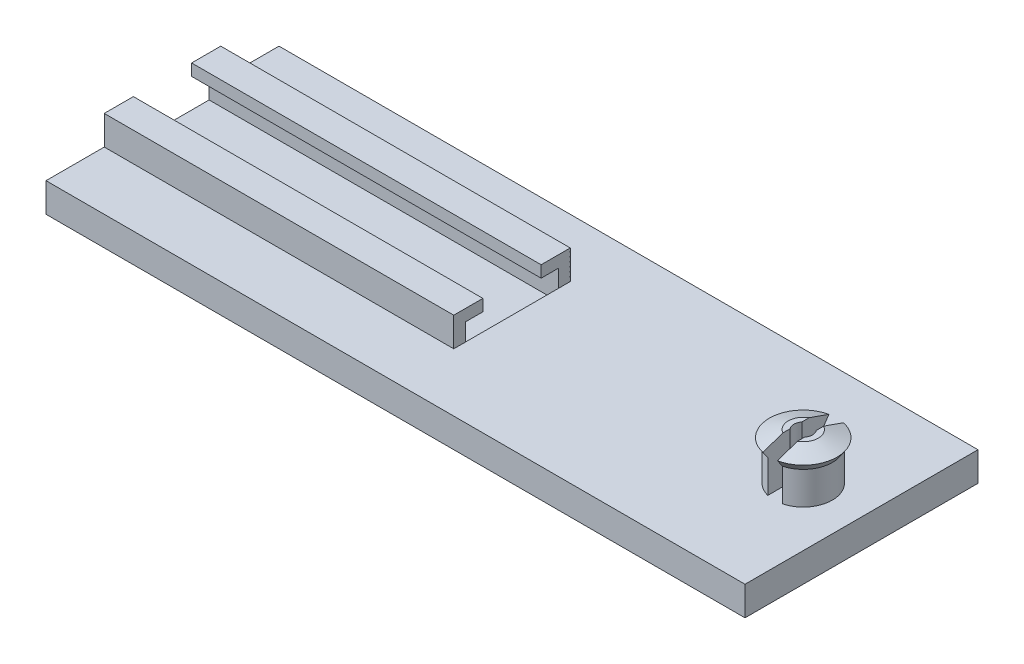
SolidWorks part; units mm, degrees
ref_plane "Front Plane" through (0, 0, 0) normal (0, 0, 1) x (1, 0, 0)
ref_plane "Top Plane" through (0, 0, 0) normal (0, 1, 0) x (1, 0, 0)
ref_plane "Right Plane" through (0, 0, 0) normal (1, 0, 0) x (0, 0, -1)
sketch "Sketch3" plane through (0, 0, 0) normal (0, 1, 0) x (1, 0, 0)
  line L1 (-38.1, -12.7) -> (38.1, -12.7)
  line L2 (-38.1, -12.7) -> (-38.1, 12.7)
  line L3 (-38.1, 12.7) -> (38.1, 12.7)
  line L4 (38.1, -12.7) -> (38.1, 12.7)
  line L5 (-38.1, -12.7) -> (38.1, 12.7) construction
  line L6 (-38.1, 12.7) -> (38.1, -12.7) construction
  point P0 (0, 0)
  dimension "D1" = 25.4
  dimension "D2" = 76.2
extrude "Boss-Extrude1" add sketch "Sketch3" along normal blind 3.175
sketch "Sketch4" plane through (0, 3.175, 0) normal (0, 1, 0) x (1, 0, 0)
  line L0 (-38.1, 12.7) -> (-38.1, -12.7) construction
  line L1 (-38.1, -6.35) -> (0, -6.35)
  line L2 (-38.1, -6.35) -> (-38.1, 6.35)
  line L3 (-38.1, 6.35) -> (0, 6.35)
  line L4 (0, -6.35) -> (0, 6.35)
  line L5 (38.1, 12.7) -> (-38.1, 12.7) construction
  line L6 (-38.1, -12.7) -> (38.1, -12.7) construction
  circle A0 centre (29.9385, 0) radius 3.175
  dimension "D1" = 6.35
  dimension "D2" = 6.35
  dimension "D3" = 6.35
  dimension "D4" = 38.1
extrude "Boss-Extrude2" add sketch "Sketch4" along normal blind 3.175 contours L2 L1 L4 L3
sketch "Sketch5" plane through (0, 3.175, 0) normal (0, 1, 0) x (1, 0, 0)
  circle A0 centre (31.75, 0) radius 3.175
  dimension "D1" = 6.35
  dimension "D2" = 31.75
sketch "Sketch6" plane through (-38.1, 0, 0) normal (-1, 0, 0) x (0, 0, 1)
  line L0 (-5.08, 1.905) -> (-5.08, 5.08)
  line L1 (-5.08, 5.08) -> (-3.175, 5.08)
  line L2 (-3.175, 5.08) -> (-3.175, 6.35)
  line L3 (6.35, 6.35) -> (-6.35, 6.35) construction
  line L4 (-3.175, 6.35) -> (3.175, 6.35)
  line L5 (3.175, 6.35) -> (3.175, 5.08)
  line L6 (3.175, 5.08) -> (5.08, 5.08)
  line L7 (5.08, 5.08) -> (5.08, 1.905)
  line L8 (5.08, 1.905) -> (-5.08, 1.905)
  line L9 (-6.35, 6.35) -> (-6.35, 3.175) construction
  line L10 (6.35, 6.35) -> (6.35, 3.175) construction
  dimension "D1" = 1.27
  dimension "D2" = 1.27
  dimension "D3" = 1.27
  dimension "D4" = 1.27
  dimension "D5" = 3.175
  dimension "D6" = 3.175
  dimension "D7" = 3.175
  dimension "D8" = 10.16
  dimension "D9" = 6.35
extrude "Cut-Extrude1" cut sketch "Sketch6" against normal blind 38.1 contours L8 L0 L1 L2 L4 L5 L6 L7
sketch "Sketch11" plane through (0, 0, 0) normal (0, 0, 1) x (1, 0, 0)
  line L0 (31.75, 3.175) -> (31.75, 12.04) construction
  line L1 (34.925, 3.175) -> (28.575, 3.175) construction
  line L2 (30.734, 3.175) -> (28.575, 3.175)
  line L3 (28.575, 3.175) -> (28.575, 6.731)
  line L4 (28.575, 6.731) -> (28.067, 7.493)
  line L5 (28.067, 7.493) -> (30.1164, 8.255)
  line L6 (30.1164, 8.255) -> (30.734, 8.255)
  line L7 (30.734, 8.255) -> (30.734, 3.175)
  point P6 (26.7679, 6.6757)
  point P11 (0, 0)
  point P12 (0, 0)
  dimension "D1" = 5.08
  dimension "D2" = 3.556
  dimension "D3" = 0.762
  dimension "D4" = 3.175
  dimension "D5" = 0.508
  dimension "D6" = 1.016
revolve "Revolve1" add sketch "Sketch11" angle 360 about L0
sketch "Sketch12" plane through (0, 0, 0) normal (0, 0, 1) x (1, 0, 0)
  line L0 (33.3836, 8.255) -> (30.1164, 8.255) construction
  line L1 (30.9563, 13.335) -> (32.5438, 13.335)
  line L2 (30.9563, 13.335) -> (30.9563, 3.175)
  line L3 (30.9563, 3.175) -> (32.5438, 3.175)
  line L4 (32.5438, 13.335) -> (32.5438, 3.175)
  line L5 (30.9563, 13.335) -> (32.5438, 3.175) construction
  line L6 (30.9563, 3.175) -> (32.5438, 13.335) construction
  line L7 (34.925, 3.175) -> (28.575, 3.175) construction
  point P0 (31.75, 8.255)
  dimension "D1" = 1.5875
extrude "Cut-Extrude3" cut sketch "Sketch12" against normal through all both and the other way through all
